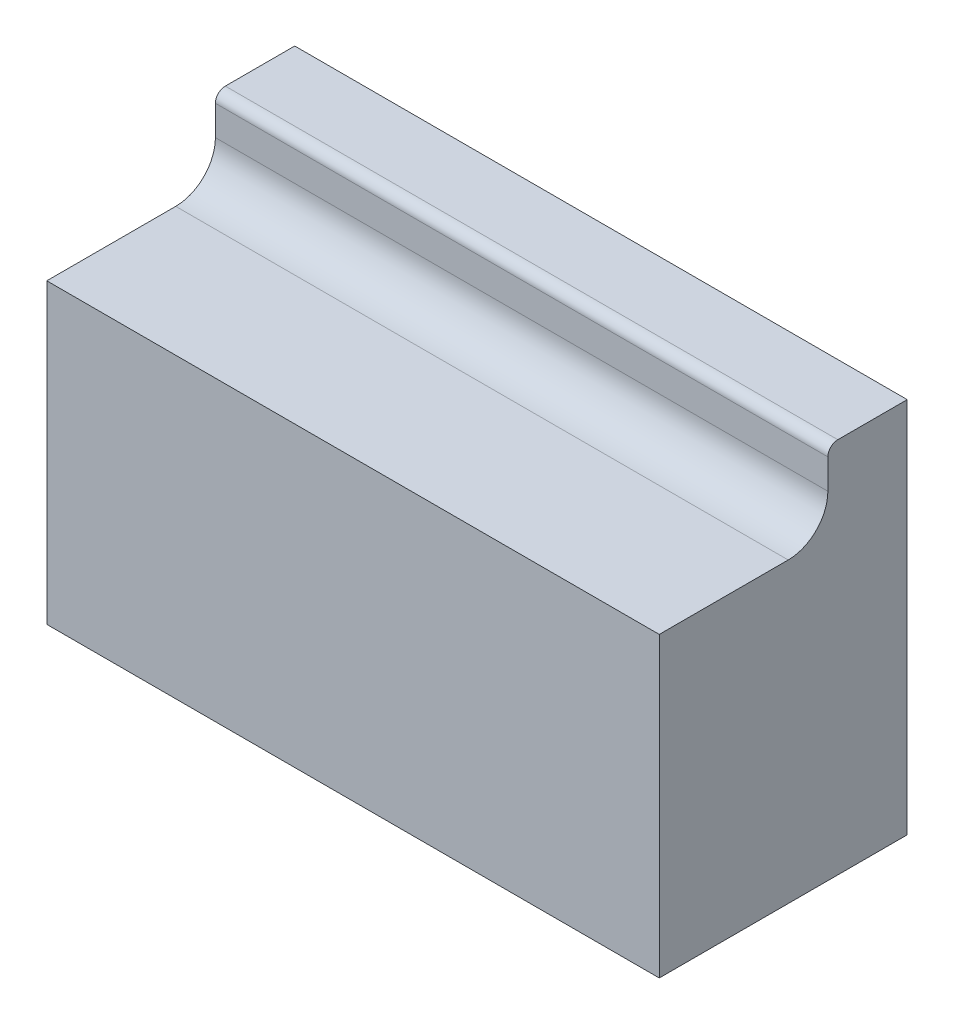
SolidWorks part; units mm, degrees
material "K110"
ref_plane "Front Plane" through (0, 0, 0) normal (0, 0, 1) x (1, 0, 0)
ref_plane "Top Plane" through (0, 0, 0) normal (0, 1, 0) x (1, 0, 0)
ref_plane "Right Plane" through (0, 0, 0) normal (1, 0, 0) x (0, 0, -1)
sketch "Sketch1" plane through (0, 0, 0) normal (0, 0, 1) x (1, 0, 0)
  line L1 (5.7154, -38) -> (67.4654, -38)
  line L2 (5.7154, -38) -> (5.7154, 0)
  line L3 (5.7154, 0) -> (67.4654, 0)
  line L4 (67.4654, -38) -> (67.4654, 0)
  dimension "D1" = 38
  dimension "D2" = 61.75
extrude "Boss-Extrude1" add sketch "Sketch1" along normal mid plane 25
sketch "Sketch2" plane through (67.4654, 0, 0) normal (1, 0, 0) x (0, 0, -1)
  line L0 (-12.5, -8) -> (0.5, -8)
  line L1 (-12.5, -38) -> (-12.5, 0) construction
  line L2 (4.5, -4) -> (4.5, 0)
  line L3 (-12.5, 0) -> (12.5, 0) construction
  line L4 (4.5, 0) -> (-12.5, 0)
  line L5 (-12.5, 0) -> (-12.5, -8)
  line L6 (0.5, -8) -> (0.5, -6) construction
  line L7 (1.809, -8) -> (-53.191, -8) construction
  arc A0 (0.5, -8) -> (4.5, -4) centre (0.5, -4) ccw
  arc A1 (0.5, -8) -> (2.5, -7.4641) centre (0.5, -4) ccw construction
  point P9 (4.5, -8)
extrude "Cut-Extrude1" cut sketch "Sketch2" against normal up to next
fillet "Fillet1" radius 1 1 edges at (36.5904, 0, -4.5)
hole_wizard "M6 Tapped Hole1" positions "Sketch5" profile "Sketch4" tap size "M6" standard "ISO"
sketch "Sketch5" plane through (0, -38, 0) normal (0, -1, 0) x (-1, 0, 0)
  line L0 (-36.5904, 12.5) -> (-36.5904, -12.5) construction
  line L1 (-67.4654, 12.5) -> (-5.7154, 12.5) construction
  line L2 (-5.7154, -12.5) -> (-67.4654, -12.5) construction
  line L4 (-67.4654, 0) -> (-5.7154, 0) construction
  line L5 (-67.4654, -12.5) -> (-67.4654, 12.5) construction
  line L6 (-5.7154, 12.5) -> (-5.7154, -12.5) construction
  point P0 (-57.5904, 0)
  point P2 (-15.5904, 0)
  dimension "D1" = 42
sketch "Sketch4" plane through (57.5904, -38, 0) normal (1, 0, 0) x (0, 0, -1)
  line L0 (0, 0) -> (0, 18.5022)
  line L1 (0, 18.5022) -> (2.5, 17)
  line L2 (2.5, 17) -> (2.5, 0)
  line L5 (2.5, 0) -> (0, 0)
  line L10 (0, 18.5022) -> (-2.5, 17) construction
  line L11 (0, -6.35) -> (0, 107.95) construction
  dimension "Tap Drill Dia." = 5
  dimension "Tap Drill Depth" = 17
  dimension "Drill Angle" = 118
cosmetic thread "Hole Thread1"
cosmetic thread "Hole Thread2"
